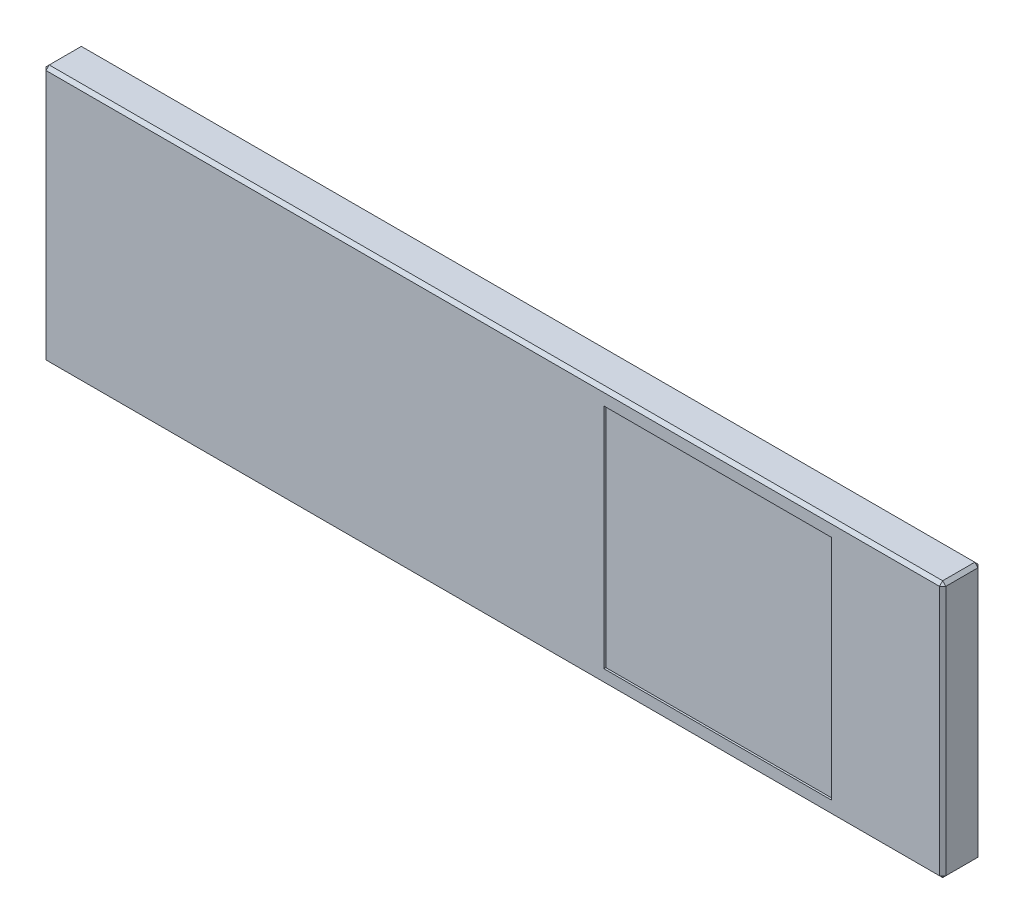
SolidWorks part; units mm, degrees
ref_plane "Alzado" through (0, 0, 0) normal (0, 0, 1) x (1, 0, 0)
ref_plane "Planta" through (0, 0, 0) normal (0, 1, 0) x (1, 0, 0)
ref_plane "Vista lateral" through (0, 0, 0) normal (1, 0, 0) x (0, 0, -1)
sketch "Croquis1" plane through (0, 0, 0) normal (0, 0, 1) x (1, 0, 0)
  line L0 (-70, 0) -> (70, 0)
  line L1 (70, 0) -> (70, 40)
  line L2 (70, 40) -> (-70, 40)
  line L3 (-70, 40) -> (-70, 0)
extrude "Saliente-Extruir1" add sketch "Croquis1" along normal mid plane 6
chamfer "Chaflán1" distance 0.5 angle 45 12 edges at (-70, 20, -3) (0, 0, -3) (70, 20, -3) (0, 40, -3) (-70, 20, 3) (-70, 40, 0) (0, 40, 3) (70, 40, 0) (70, 20, 3) (70, 0, 0) (0, 0, 3) (-70, 0, 0)
ref_plane "Plano cara lisa" through (0, 0, 3) normal (0, 0, 1) x (1, 0, 0)
ref_plane "Plano cara aleta" through (0, 0, -3) normal (0, 0, 1) x (1, 0, 0)
sketch "Croquis4" plane through (0, 0, -3) normal (0, 0, 1) x (1, 0, 0)
  line L0 (-55, 17.5) -> (-15, 17.5)
  line L1 (-15, 17.5) -> (-15, 22.5)
  line L2 (-15, 22.5) -> (-55, 22.5)
  line L3 (-55, 22.5) -> (-55, 17.5)
extrude "Saliente-Extruir3" add sketch "Croquis4" against normal blind 18
chamfer "Chaflán2" distance 1.5 angle 45 4 edges at (-55, 20, -21) (-35, 17.5, -21) (-15, 20, -21) (-35, 22.5, -21)
fillet "Redondeo1" radius 2 4 edges at (-55, 20, -3) (-35, 17.5, -3) (-15, 20, -3) (-35, 22.5, -3)
sketch "Croquis5" plane through (0, 0, 0) normal (0, 1, 0) x (1, 0, 0)
  circle A0 centre (-50, 0) radius 2.15
  circle A1 centre (0, 0) radius 2.15
  circle A2 centre (50, 0) radius 2.15
sketch "Croquis6" plane through (0, 0, 3) normal (0, 0, 1) x (1, 0, 0)
  line L0 (17.3, 2.3) -> (52.7, 2.3)
  line L1 (52.7, 2.3) -> (52.7, 37.7)
  line L2 (52.7, 37.7) -> (17.3, 37.7)
  line L3 (17.3, 37.7) -> (17.3, 2.3)
sketch "Croquis7" plane through (0, 0, -3) normal (0, 0, 1) x (1, 0, 0)
  line L0 (17.3, 2.3) -> (52.7, 2.3)
  line L1 (52.7, 2.3) -> (52.7, 37.7)
  line L2 (52.7, 37.7) -> (17.3, 37.7)
  line L3 (17.3, 37.7) -> (17.3, 2.3)
sketch "Croquis8" plane through (0, 0, -3) normal (0, 0, 1) x (1, 0, 0)
  line L0 (-38, 9) -> (-32, 9)
  line L1 (-32, 9) -> (-35, 3)
  line L2 (-35, 3) -> (-38, 9)
extrude "Cortar-Extruir1" cut sketch "Croquis5" along normal blind 4.3
extrude "Cortar-Extruir3" cut sketch "Croquis6" against normal blind 0.3
extrude "Cortar-Extruir5" cut sketch "Croquis7" along normal blind 0.3
extrude "Cortar-Extruir6" cut sketch "Croquis8" along normal blind 0.4
